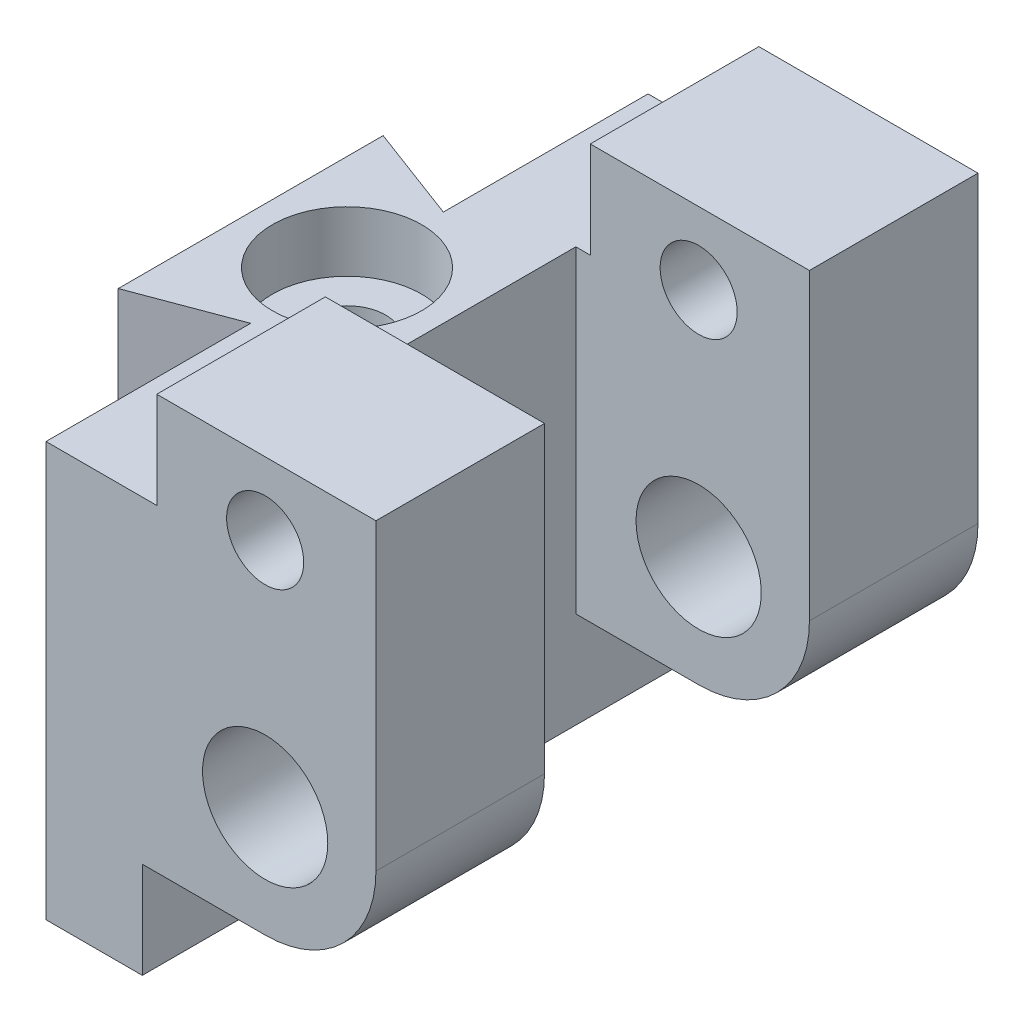
SolidWorks part; units mm, degrees
ref_plane "Alzado" through (0, 0, 0) normal (0, 0, 1) x (1, 0, 0)
ref_plane "Planta" through (0, 0, 0) normal (0, 1, 0) x (1, 0, 0)
ref_plane "Vista lateral" through (0, 0, 0) normal (1, 0, 0) x (0, 0, -1)
sketch "Croquis1" plane through (0, 0, 0) normal (0, 0, 1) x (1, 0, 0)
  line L0 (-9.1, 0) -> (0, 0) construction
  line L1 (-9.1, 8.6) -> (-5.1, 8.6)
  line L2 (-9.1, 8.6) -> (-9.1, -8.6)
  line L3 (-9.1, -8.6) -> (-5.1, -8.6)
  line L4 (-5.1, 8.6) -> (-5.1, 4.6)
  line L5 (0, 4.6) -> (-5.1, 4.6)
  line L6 (0, -4.6) -> (-5.1, -4.6)
  line L7 (-5.1, -4.6) -> (-5.1, -8.6)
  circle A0 centre (0, 0) radius 2.6
  arc A1 (0, -4.6) -> (0, 4.6) centre (0, 0) ccw
  dimension "D1" = 5.2
  dimension "D2" = 2
  dimension "D3" = 4
  dimension "D4" = 4
  dimension "D5" = 9.1
extrude "Saliente-Extruir1" add sketch "Croquis1" along normal blind 25
sketch "Croquis2" plane through (0, 4.6, 0) normal (0, 1, 0) x (1, 0, 0)
  line L0 (-5.1, -25) -> (-5.1, 0) construction
  line L1 (-5.1, -18) -> (4.6, -18)
  line L2 (-5.1, -18) -> (-5.1, -7)
  line L3 (-5.1, -7) -> (4.6, -7)
  line L4 (4.6, -18) -> (4.6, -7)
  line L5 (4.6, -25) -> (4.6, 0) construction
  line L6 (-5.1, -12.5) -> (-9.1, -12.5) construction
  line L7 (-9.1, -25) -> (-9.1, 0) construction
  dimension "D1" = 11
extrude "Cortar-Extruir1" cut sketch "Croquis2" against normal blind 25
sketch "Croquis3" plane through (0, 8.6, 0) normal (0, 1, 0) x (1, 0, 0)
  line L0 (-9.1, -25) -> (-9.1, 0) construction
  line L1 (-9.1, -16.5) -> (-13.1, -16.5)
  line L2 (-9.1, -16.5) -> (-9.1, -8.5)
  line L3 (-9.1, -8.5) -> (-13.1, -8.5)
  line L4 (-13.1, -16.5) -> (-13.1, -8.5)
  line L5 (-13.1, -12.5) -> (-5.1, -12.5) construction
  line L6 (-5.1, -25) -> (-5.1, 0) construction
  dimension "D1" = 8
  dimension "D2" = 8
extrude "Saliente-Extruir2" add sketch "Croquis3" against normal up to surface (17.2 mm away) up to face at (-7.1, -8.6, 12.5)
ref_plane "Plano1" through (0, -0.6, 0) normal (0, -1, 0) x (-1, 0, 0)
sketch "Croquis4" plane through (0, -0.6, 0) normal (0, -1, 0) x (-1, 0, 0)
  line L0 (13.1, -16.5) -> (5.1, -8.5) construction
  line L1 (5.1, -25) -> (5.1, 0) construction
  line L2 (5.1, -8.5) -> (9.1, -8.5) construction
  line L3 (7.0123, -9.75) -> (5.1, -9.75)
  line L5 (7.0123, -15.25) -> (10.6877, -15.25)
  line L6 (10.6877, -15.25) -> (12.2754, -12.5)
  line L7 (12.2754, -12.5) -> (10.6877, -9.75)
  line L8 (10.6877, -9.75) -> (7.0123, -9.75)
  line L10 (5.1, -9.75) -> (5.1, -15.25)
  line L11 (5.1, -15.25) -> (7.0123, -15.25)
  line L13 (7.0869, -10.4869) -> (6.7184, -11.125) [skipped]
  line L14 (6.8684, -14.1348) -> (7.6623, -15.5098) [skipped]
  circle A0 centre (9.1, -12.5) radius 2.75 construction
  dimension "D1" = 5.5
extrude "Cortar-Extruir2" cut sketch "Croquis4" against normal blind 1.25 and the other way blind 1.25
sketch "Croquis5" plane through (0, -8.6, 0) normal (0, -1, 0) x (1, 0, 0)
  line L0 (-9.1, 8.5) -> (-5.1, 8.5) construction
  line L1 (-5.1, 25) -> (-5.1, 0) construction
  line L2 (-5.1, 8.5) -> (-13.1, 16.5) construction
  circle A0 centre (-9.1, 12.5) radius 1.6
  dimension "D1" = 3.2
extrude "Cortar-Extruir3" cut sketch "Croquis5" against normal blind 34.25
sketch "Croquis6" plane through (0, -8.6, 0) normal (0, -1, 0) x (1, 0, 0)
  line L0 (-13.1, 16.5) -> (-13.1, 18)
  line L1 (-13.1, 18) -> (-9.1, 16.5)
  line L2 (-9.1, 16.5) -> (-13.1, 16.5)
  line L3 (-13.1, 8.5) -> (-13.1, 7)
  line L4 (-13.1, 7) -> (-9.1, 8.5)
  line M8 (-9.1, 16.5) -> (-13.1, 16.5)
  line M10 (-13.1, 8.5) -> (-9.1, 8.5)
  dimension "D1" = 1.5
extrude "Saliente-Extruir3" add sketch "Croquis6" against normal up to surface (17.2 mm away) contours L1 L0 M8 | L3 L4 M10 up to face at (-9.1, 8.6, 10.9)
sketch "Croquis12" plane through (0, 0, 25) normal (0, 0, 1) x (1, 0, 0)
  line L0 (1.9, 11.6) -> (4.6, 11.6)
  line L1 (-5.1, 4.6) -> (0, 4.6)
  line L2 (-5.1, 4.6) -> (-5.1, 11.6)
  line L3 (-5.1, 11.6) -> (1.9, 11.6)
  line L5 (4.6, 11.6) -> (4.6, 0)
  line L6 (0, 4.6) -> (0, 4)
  line L7 (4, 0) -> (4.6, 0)
  arc A0 (0, -4.6) -> (0, 4.6) centre (0, 0) ccw construction
  arc A1 (4, 0) -> (0, 4) centre (0, 0) ccw
  dimension "D2" = 4
  dimension "D1" = 7
extrude "Saliente-Extruir4" add sketch "Croquis12" against normal up to surface (25 mm away) up to face at (-4.25, 0, 0)
sketch "Croquis13" plane through (0, 4.6, 0) normal (0, -1, 0) x (1, 0, 0)
  line L1 (-5.1, 7) -> (4.6, 7)
  line L2 (-5.1, 7) -> (-5.1, 18)
  line L6 (-5.1, 18) -> (4.6, 18)
  line L7 (4.6, 18) -> (4.6, 7)
extrude "Cortar-Extruir4" cut sketch "Croquis13" against normal blind 27.25 and the other way blind 27.25
sketch "Croquis15" plane through (0, 0, 25) normal (0, 0, 1) x (1, 0, 0)
  line L0 (0, 0) -> (0, 9.6) construction
  line L1 (-5.1, 11.6) -> (1.5087, 11.6) construction
  line L2 (-5.1, 11.6) -> (-5.1, 4.9913) construction
  circle A0 centre (0, 9.6) radius 1.6
  dimension "D1" = 2
  dimension "D2" = 3.2
extrude "Cortar-Extruir6" cut sketch "Croquis15" against normal blind 27.25
sketch "Croquis16" plane through (0, 0, 25) normal (0, 0, 1) x (1, 0, 0)
  line L0 (-5.1, 8.6) -> (-9.1, 8.6) construction
  line L1 (-5.1, 11.6) -> (-4.5, 11.6)
  line L2 (-5.1, 11.6) -> (-5.1, 8.6)
  line L3 (-5.1, 8.6) -> (-4.5, 8.6)
  line L4 (-4.5, 11.6) -> (-4.5, 8.6)
  dimension "D1" = 0.6
extrude "Cortar-Extruir7" cut sketch "Croquis16" against normal blind 33
sketch "Croquis17" plane through (0, 8.6, 0) normal (0, 1, 0) x (1, 0, 0)
  circle A0 centre (-9.1, -12.5) radius 3.1
  dimension "D1" = 6.2
extrude "Cortar-Extruir8" cut sketch "Croquis17" against normal blind 2.5
sketch "Croquis18" plane through (0, 11.6, 0) normal (0, 1, 0) x (1, 0, 0)
  line L4 (-4.5, -18) -> (-4.5, -25)
  line L5 (-4.5, -25) -> (4.6, -25)
  line L6 (4.6, -25) -> (4.6, -18)
  line L7 (4.6, -18) -> (-4.5, -18)
  line L8 (-4.5, -18) -> (-4.5, -25)
  line L9 (-4.5, -25) -> (4.6, -25)
  line L10 (4.6, -25) -> (4.6, -18)
  line L11 (4.6, -18) -> (-4.5, -18)
  line L12 (-4.5, 0) -> (-4.5, -7)
  line L13 (-4.5, -7) -> (4.6, -7)
  line L14 (4.6, -7) -> (4.6, 0)
  line L15 (4.6, 0) -> (-4.5, 0)
  line L16 (-4.5, 0) -> (-4.5, -7)
  line L17 (-4.5, -7) -> (4.6, -7)
  line L18 (4.6, -7) -> (4.6, 0)
  line L19 (4.6, 0) -> (-4.5, 0)
  dimension "D1" = 0
  dimension "D2" = 0
extrude "Saliente-Extruir5" add sketch "Croquis18" along normal blind 1
